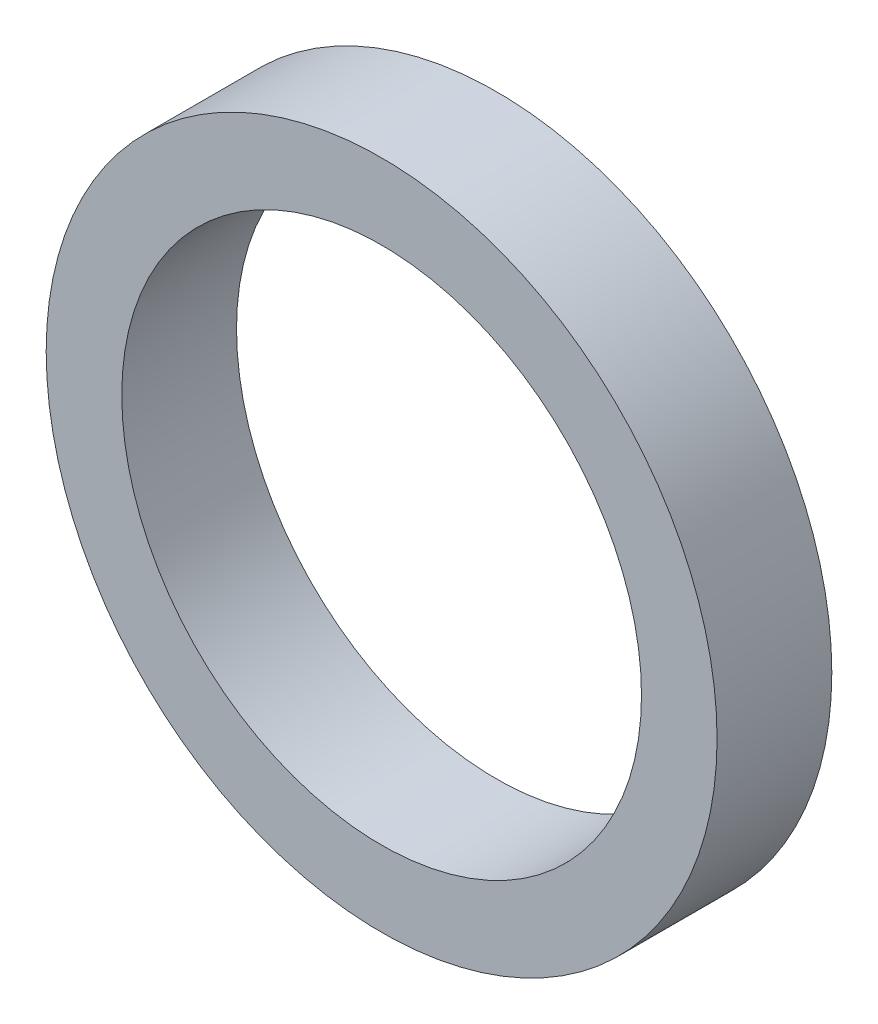
SolidWorks part; units mm, degrees
ref_plane "Front Plane" through (0, 0, 0) normal (0, 0, 1) x (1, 0, 0)
ref_plane "Top Plane" through (0, 0, 0) normal (0, 1, 0) x (1, 0, 0)
ref_plane "Right Plane" through (0, 0, 0) normal (1, 0, 0) x (0, 0, -1)
sketch "Sketch1" plane through (0, 0, 0) normal (0, 0, 1) x (1, 0, 0)
  circle A0 centre (0, 0) radius 278.5
  circle A1 centre (0, 0) radius 215.7488
  dimension "D1" = 557
extrude "Boss-Extrude1" add sketch "Sketch1" along normal up to vertex (47.4784 mm away) and the other way up to vertex (47.7889 mm away) contours A0 A1
